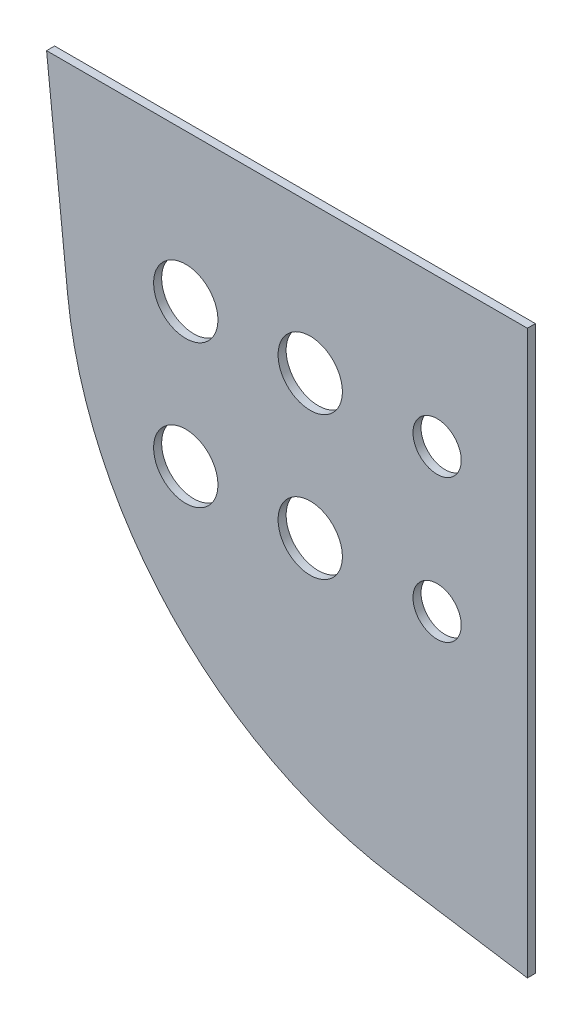
SolidWorks part; units mm, degrees
material "Custom Plastic"
ref_plane "X-Y Datum" through (0, 0, 0) normal (0, 0, 1) x (1, 0, 0)
ref_plane "X-Z Datum" through (0, 0, 0) normal (0, 1, 0) x (1, 0, 0)
ref_plane "Y-Z Datum" through (0, 0, 0) normal (1, 0, 0) x (0, 0, -1)
sketch "Sketch1" plane through (0, 0, 0) normal (0, 0, 1) x (1, 0, 0)
  line L10 (-132.424, 190.9765) -> (-145.9943, 61.7926)
  line L11 (-132.424, 190.9765) -> (-145.9943, 61.7926)
  line L12 (96.4882, 293.3455) -> (-57.5815, 269.547)
  line L13 (272.8986, 235.8261) -> (143.226, 287.9689)
  line L14 (374.2192, 188.6716) -> (276.6913, 234.1801)
  line L15 (374.2192, -83.6616) -> (374.2192, 188.6716)
  line L16 (374.2192, -83.6616) -> (276.6913, -129.1701)
  line L17 (272.8986, -130.8161) -> (143.226, -182.9589)
  line L18 (96.4882, -188.3355) -> (-57.5815, -164.5369)
  line L19 (-132.424, -85.9665) -> (-145.9943, 43.2174)
  line L20 (-132.8098, -44.9665) -> (35.942, 52.505)
  line L21 (35.942, 52.505) -> (-132.8098, 149.9765)
  line L22 (-142.3821, -28.4961) -> (-2.8927, 52.505)
  line L23 (-2.8927, 52.505) -> (-142.3821, 133.5061)
  line L24 (98.4269, -175.7843) -> (-55.6428, -151.9858)
  line L25 (-119.7935, -84.6397) -> (-133.3638, 44.5442)
  line L26 (-29.0041, -156.1006) -> (-29.0041, 14.992)
  line L27 (-132.8098, -44.9665) -> (-29.0041, -44.9665)
  arc A7 (-57.5815, 269.547) -> (-132.424, 190.9765) centre (-44.0104, 181.6889) ccw
  arc A8 (143.226, 287.9689) -> (96.4882, 293.3455) centre (110.0593, 205.4875) ccw
  arc A9 (276.6913, 234.1801) -> (272.8986, 235.8261) centre (244.4701, 165.1277) ccw
  arc A10 (272.8986, -130.8161) -> (276.6913, -129.1701) centre (244.4701, -60.1177) ccw
  arc A11 (96.4882, -188.3355) -> (143.226, -182.9589) centre (110.0593, -100.4775) ccw
  arc A12 (-132.424, -85.9665) -> (-57.5815, -164.5369) centre (-44.0104, -76.6789) ccw
  arc A13 (-145.9943, 61.7926) -> (-145.9943, 43.2174) centre (-57.5808, 52.505) ccw
  arc A14 (-119.7935, -84.6397) -> (-55.6428, -151.9858) centre (-44.0104, -76.6789) ccw
  ellipse E2 centre (-137.596, 141.7413) end of major axis (-133.6394, 148.5491) minor radius 4.7108
  ellipse E4 centre (-137.596, 141.7413) end of major axis (-132.8098, 149.9765) minor radius 5.6986
  ellipse E7 centre (-137.596, -36.7313) end of major axis (-141.5525, -29.9235) minor radius 4.7108
  ellipse E9 centre (-137.596, -36.7313) end of major axis (-142.3821, -28.4961) minor radius 5.6986
  dimension "D1" = 12.7
extrude "Boss-Extrude1" add sketch "Sketch1" along normal blind 1.5875 contours L25 A14 L24 L26 L27
sketch "Sketch2" plane through (0, 0, 0) normal (0, 0, -1) x (-1, 0, 0)
  circle A1 centre (71.8925, -102.3153) radius 6.35
  circle A3 centre (96.4752, -102.3153) radius 6.35
  circle A5 centre (96.4752, -74.1072) radius 6.35
  circle A6 centre (71.8925, -74.1072) radius 6.35
  circle A7 centre (96.4752, -102.3153) radius 9.525 construction
  circle A8 centre (96.4752, -74.1072) radius 9.525 construction
  circle A9 centre (71.8925, -102.3153) radius 9.525 construction
  circle A10 centre (71.8925, -74.1072) radius 9.525 construction
  circle A11 centre (46.8316, -102.3153) radius 4.7625
  circle A12 centre (46.8316, -74.1072) radius 4.7625
  circle A13 centre (46.8316, -102.3153) radius 7.9375 construction
  circle A14 centre (46.8316, -74.1072) radius 7.9375 construction
  point P18 (69.8642, -103.0901)
  point P19 (0, 0)
  point P20 (95.7008, -74.1072)
  point P21 (71.3939, -102.4067)
  point P22 (96.4752, -102.3153)
  point P23 (0, 0)
  point P24 (0, 0)
  point P25 (71.8925, -74.1072)
  point P26 (46.8316, -102.3153)
  point P27 (46.8316, -74.1072)
  dimension "D1" = 12.7
  dimension "D2" = 19.05
  dimension "D3" = 9.525
  dimension "D4" = 15.875
extrude "Cut-Extrude1" cut sketch "Sketch2" against normal through all
